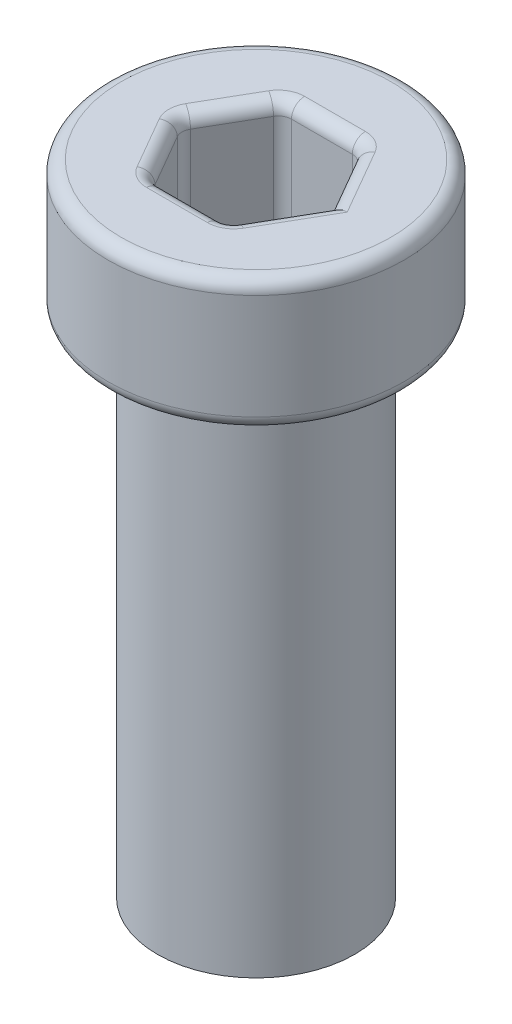
SolidWorks part; units mm, degrees
material "201 Annealed Stainless Steel (SS)"
ref_plane "Front Plane" through (0, 0, 0) normal (0, 0, 1) x (1, 0, 0)
ref_plane "Top Plane" through (0, 0, 0) normal (0, 1, 0) x (1, 0, 0)
ref_plane "Right Plane" through (0, 0, 0) normal (1, 0, 0) x (0, 0, -1)
sketch "Master Sketch" plane through (0, 0, 0) normal (0, 1, 0) x (1, 0, 0)
  line L1 (0.5774, 1) -> (-0.5774, 1)
  line L2 (-0.5774, 1) -> (-1.1547, 0)
  line L3 (-1.1547, 0) -> (-0.5774, -1)
  line L4 (-0.5774, -1) -> (0.5774, -1)
  line L5 (0.5774, -1) -> (1.1547, 0)
  line L6 (1.1547, 0) -> (0.5774, 1)
  circle A0 centre (0, 0) radius 2.25
  circle A1 centre (0, 0) radius 1 construction
  circle A2 centre (0, 0) radius 1.5
  dimension "D1" = 4.5
  dimension "D2" = 2
  dimension "D3" = 3
sketch "Head Sketch" plane through (0, 0, 0) normal (0, 1, 0) x (1, 0, 0)
  line L0 (-0.5774, 1) -> (-1.1547, 0) construction
  line L1 (-0.5774, 1) -> (-1.1547, 0)
  line L2 (-1.1547, 0) -> (-0.5774, -1) construction
  line L3 (-0.5774, -1) -> (0.5774, -1) construction
  line L4 (0.5774, -1) -> (1.1547, 0) construction
  line L5 (0.5774, 1) -> (-0.5774, 1) construction
  line L6 (1.1547, 0) -> (0.5774, 1) construction
  line L7 (-1.1547, 0) -> (-0.5774, -1)
  line L8 (-0.5774, -1) -> (0.5774, -1)
  line L9 (0.5774, -1) -> (1.1547, 0)
  line L10 (0.5774, 1) -> (-0.5774, 1)
  line L11 (1.1547, 0) -> (0.5774, 1)
  circle A0 centre (0, 0) radius 2.25 construction
  circle A1 centre (0, 0) radius 2.25
extrude "Head" add sketch "Head Sketch" along normal blind 2
sketch "Threaded Section Stub Sketch" plane through (0, 0, 0) normal (0, 1, 0) x (1, 0, 0)
  circle A0 centre (0, 0) radius 1.5 construction
  circle A1 centre (0, 0) radius 1.5
extrude "Threaded Section" add sketch "Threaded Section Stub Sketch" against normal blind 8
cosmetic thread "Cosmetic Thread1" parameters "D2"=2.439
chamfer "End Of Bolt chamfer" distance 0.5 angle 30 1 edges at (0, -8, 1.5)
fillet "Cosmetic Fillets" radius 0.2 19 edges at (-0.5774, 1, -1) (-1.1547, 1, 0) (-0.5774, 1, 1) (0.5774, 1, 1) (0.5774, 1, -1) (0, 0, -1) (0.866, 0, -0.5) (-0.866, 0, -0.5) (-0.866, 0, 0.5) (0.866, 0, 0.5) (0, 0, 1) (0.866, 2, -0.5) (0.866, 2, 0.5) (0, 2, -1) (0, 2, 1) (-0.866, 2, 0.5) (-0.866, 2, -0.5) (0, 0, 2.25) (0, 2, 2.25)
